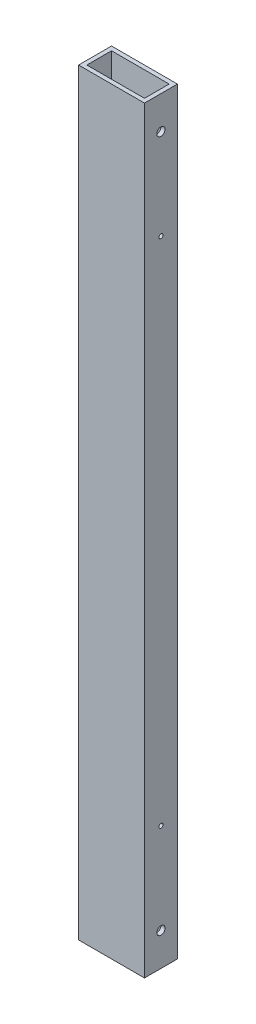
SolidWorks part; units mm, degrees
material "1060 Alloy"
ref_plane "Front Plane" through (0, 0, 0) normal (0, 0, 1) x (1, 0, 0)
ref_plane "Top Plane" through (0, 0, 0) normal (0, 1, 0) x (1, 0, 0)
ref_plane "Right Plane" through (0, 0, 0) normal (1, 0, 0) x (0, 0, -1)
sketch "Sketch1" plane through (0, 0, 0) normal (0, 1, 0) x (1, 0, 0)
  line L0 (-3.175, 22.225) -> (47.625, 22.225)
  line L1 (0, 0) -> (44.45, 0)
  line L2 (0, 0) -> (0, 19.05)
  line L3 (0, 19.05) -> (44.45, 19.05)
  line L4 (44.45, 0) -> (44.45, 19.05)
  line L5 (47.625, -3.175) -> (47.625, 22.225)
  line L6 (-3.175, -3.175) -> (47.625, -3.175)
  line L7 (-3.175, -3.175) -> (-3.175, 22.225)
  dimension "D2" = 25.4
  dimension "D3" = 50.8
  dimension "D1" = 3.175
extrude "Boss-Extrude1" add sketch "Sketch1" along normal blind 584.2
sketch "Sketch2" plane through (47.625, 0, 0) normal (1, 0, 0) x (0, 0, -1)
  line L0 (-3.175, 584.2) -> (22.225, 584.2) construction
  line L1 (22.225, 584.2) -> (22.225, 0) construction
  line L2 (13.97, 0) -> (-13.97, 0) construction
  circle A0 centre (9.525, 95.25) radius 1.5875
  circle A1 centre (9.525, 488.95) radius 1.5875
  dimension "D2" = 3.175
  dimension "D4" = 3.175
  dimension "D5" = 12.7
  dimension "D1" = 95.25
  dimension "D3" = 12.7
  dimension "D6" = 95.25
extrude "Cut-Extrude1" cut sketch "Sketch2" against normal through all
sketch "Sketch3" plane through (-3.175, 0, 0) normal (-1, 0, 0) x (0, 0, 1)
  line L0 (-22.225, 584.2) -> (3.175, 584.2) construction
  line L1 (3.175, 584.2) -> (3.175, 0) construction
  line L2 (-22.225, 0) -> (3.175, 0) construction
  line L3 (-22.225, 584.2) -> (-22.225, 0) construction
  circle A0 centre (-9.525, 25.4) radius 3.175
  circle A1 centre (-9.525, 558.8) radius 3.175
  point P6 (-9.525, 584.2)
  dimension "D1" = 6.35
  dimension "D2" = 25.4
  dimension "D3" = 12.7
  dimension "D4" = 25.4
  dimension "D5" = 12.7
extrude "Cut-Extrude2" cut sketch "Sketch3" against normal through all
